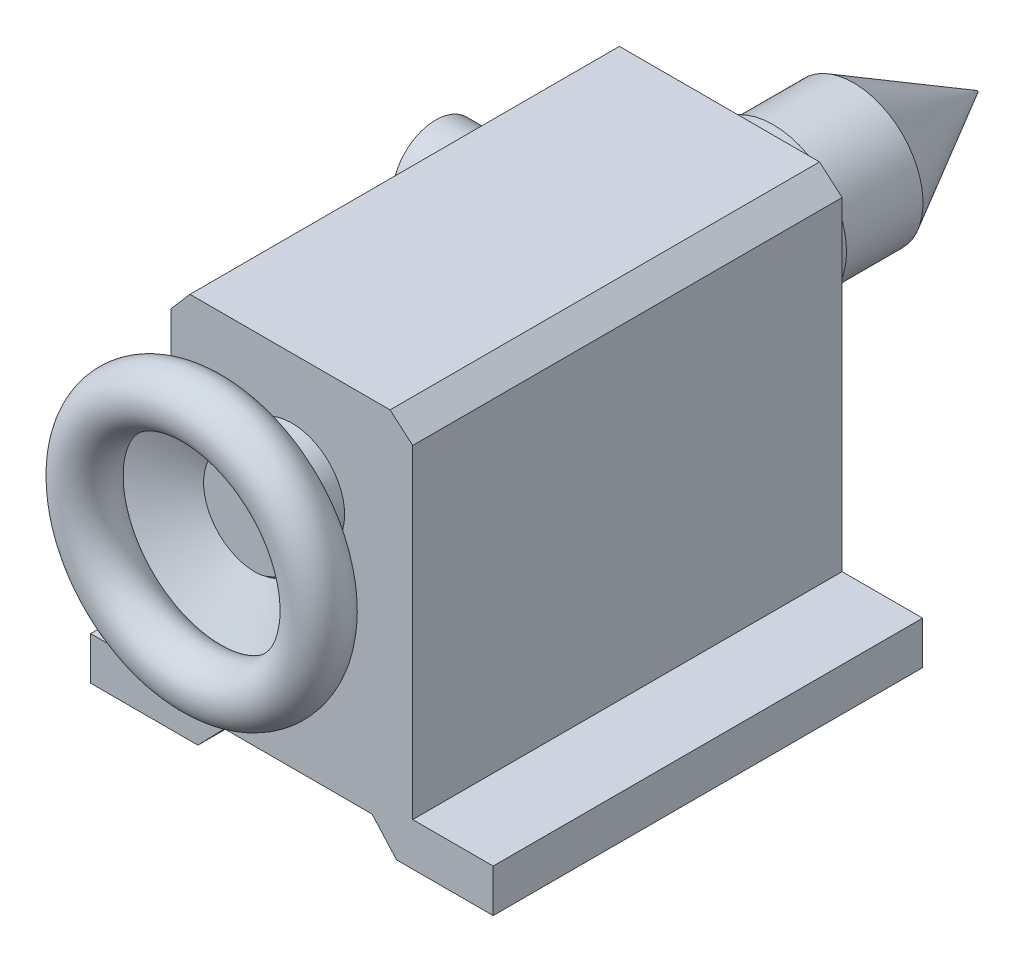
SolidWorks part; units mm, degrees
ref_plane "Front Plane" through (0, 0, 0) normal (0, 0, 1) x (1, 0, 0)
ref_plane "Top Plane" through (0, 0, 0) normal (0, 1, 0) x (1, 0, 0)
ref_plane "Right Plane" through (0, 0, 0) normal (1, 0, 0) x (0, 0, -1)
sketch "Sketch1" plane through (0, 0, 0) normal (0, 0, 1) x (1, 0, 0)
  line L0 (0, 0) -> (15, 0)
  line L1 (0, 0) -> (75, 0)
  line L2 (0, 0) -> (0, 72)
  line L3 (0, 72) -> (75, 72)
  line L4 (75, 0) -> (75, 72)
  line L5 (15, 0) -> (15, 72)
  line L6 (75, 72) -> (60.0096, 72)
  line L7 (60.0096, 72) -> (60.0096, 0)
  line L8 (60.0096, 0) -> (60.0096, 8)
  line L9 (60.0096, 8) -> (75, 8)
  line L10 (75, 8) -> (0, 8)
  line L11 (15, 0) -> (20, 0)
  line L12 (60.0096, 0) -> (57, 0)
  line L13 (25.2099, 5.1091) -> (60.0096, 5.1091)
  line L14 (60.0096, 5.1091) -> (15, 5.1091)
  line L15 (20, 0) -> (24.9359, 5.1091)
  line L16 (57, 0) -> (52.4376, 5.1091)
  line L17 (52.4376, 5.1091) -> (51.9967, 5.1091)
  line L18 (15, 72) -> (15, 67.9342)
  line L19 (15, 67.9342) -> (18.5141, 72)
  line L20 (18.5141, 72) -> (55.7979, 72)
  line L21 (55.7979, 72) -> (60.0096, 68.3598)
  dimension "D1" = 75
  dimension "D2" = 72
extrude "Boss-Extrude1" add sketch "Sketch1" along normal blind 80 contours L21 L3 L19 L5 L10 L7 | L5 L10 L2 L0 | L1 L15 L14 L5 | L14 L13 L7 L10 L5 | L16 L1 L8 L14 | L9 L7 L8 L1 L4
sketch "Sketch2" plane through (0, 0, 0) normal (0, 0, -1) x (-1, 0, 0)
  circle A0 centre (-37.156, 50.0288) radius 13.6712
extrude "Boss-Extrude2" add sketch "Sketch2" along normal blind 10
sketch "Sketch3" plane through (0, 0, -10) normal (0, 0, -1) x (-1, 0, 0)
  circle A0 centre (-37.156, 50.0288) radius 12.9139
extrude "Boss-Extrude3" add sketch "Sketch3" along normal blind 15
sketch "Sketch4" plane through (0, 0, -25) normal (0, 0, -1) x (-1, 0, 0)
  circle A0 centre (-37.156, 50.0288) radius 12.9139
extrude "Boss-Extrude4" add sketch "Sketch4" along normal blind 23 draft 29
sketch "Sketch5" plane through (15, 0, 0) normal (-1, 0, 0) x (0, 0, 1)
  circle A0 centre (17.6985, 52.6587) radius 1.5733
extrude "Boss-Extrude5" add sketch "Sketch5" along normal blind 5
sketch "Sketch6" plane through (10, 0, 0) normal (-1, 0, 0) x (0, 0, 1)
  circle A0 centre (17.6985, 52.6587) radius 8.0665
extrude "Boss-Extrude6" add sketch "Sketch6" along normal blind 8
sketch "Sketch7" plane through (0, 0, 80) normal (0, 0, 1) x (1, 0, 0)
  circle A0 centre (37.5, 50.8848) radius 9.8263
extrude "Boss-Extrude7" add sketch "Sketch7" along normal blind 8
sketch "Sketch8" plane through (0, 0, 80) normal (0, 0, 1) x (1, 0, 0)
  line L0 (38.6867, 5.1091) -> (38.6867, 32.3382)
  line L1 (52.4376, 5.1091) -> (24.9359, 5.1091) construction
  line L2 (38.6867, 32.3382) -> (40.068, 32.3382)
  line L3 (40.068, 32.3382) -> (39.3774, 22.0663)
  line L4 (39.3774, 22.0663) -> (38.6867, 22.0663)
extrude "Boss-Extrude8" add sketch "Sketch8" along normal blind 8 contours L4 L3 L2 L0
sketch "Sketch9" plane through (38.6867, 0, 0) normal (-1, 0, 0) x (0, 0, 1)
  line L4 (88, 50.9111) -> (110.7823, 50.9111)
  circle A0 centre (98, 72.7111) radius 5.089
revolve "Revolve1" add sketch "Sketch9" angle 360 about L4
sketch "Sketch10" plane through (38.6867, 0, 0) normal (-1, 0, 0) x (0, 0, 1)
  line L1 (80, 32.3382) -> (88, 32.3382)
  line L2 (80, 32.3382) -> (80, 22.0663)
  line L3 (80, 22.0663) -> (88, 22.0663)
  line L4 (88, 32.3382) -> (88, 22.0663)
extrude "Cut-Extrude1" cut sketch "Sketch10" against normal blind 8
sketch "Sketch11" plane through (0, 0, 80) normal (0, 0, 1) x (1, 0, 0)
  line L0 (38.6867, 5.1091) -> (38.6867, 10.3487)
  line L1 (52.4376, 5.1091) -> (24.9359, 5.1091) construction
  line L2 (38.6867, 10.3487) -> (39.7635, 10.3487)
  line L3 (39.7635, 10.3487) -> (39.7635, 5.1091)
  line L4 (39.7635, 5.1091) -> (38.6867, 5.1091)
extrude "Boss-Extrude9" add sketch "Sketch11" along normal blind 10
sketch "Sketch12" plane through (38.6867, 0, 0) normal (-1, 0, 0) x (0, 0, 1)
  line L0 (87.4619, 41.0584) -> (92.911, 30.0057)
  line L1 (80, 41.0584) -> (88, 41.0584) construction
  line L2 (92.911, 72.7111) -> (92.911, 29.1111) construction
  line L3 (92.911, 30.0057) -> (93.4217, 30.2575)
  line L4 (93.4217, 30.2575) -> (87.9727, 41.3102)
  line L5 (87.9727, 41.3102) -> (87.4619, 41.0584)
  line L6 (88, 50.8848) -> (94.6472, 50.8848)
  line L7 (88, 41.0584) -> (88, 60.7111) construction
revolve "Revolve2" add sketch "Sketch12" angle 360 about L6
sketch "Sketch13" plane through (38.6867, 0, 0) normal (-1, 0, 0) x (0, 0, 1)
  line L1 (90, 5.1091) -> (80, 5.1091)
  line L2 (90, 5.1091) -> (90, 10.3487)
  line L3 (90, 10.3487) -> (80, 10.3487)
  line L4 (80, 5.1091) -> (80, 10.3487)
extrude "Cut-Extrude2" cut sketch "Sketch13" against normal blind 10
